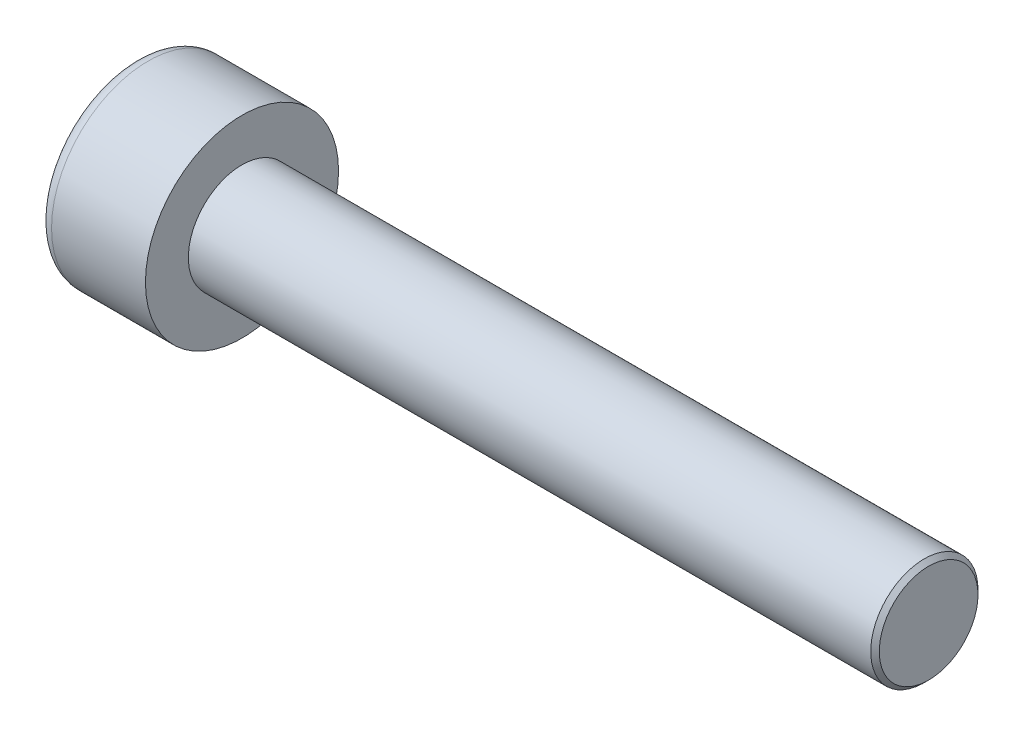
SolidWorks part; units mm, degrees
ref_plane "Front" through (0, 0, 0) normal (0, 0, 1) x (1, 0, 0)
ref_plane "Top" through (0, 0, 0) normal (0, 1, 0) x (1, 0, 0)
ref_plane "Right" through (0, 0, 0) normal (1, 0, 0) x (0, 0, -1)
sketch "Sketch1" plane through (0, 0, 0) normal (1, 0, 0) x (0, 0, -1)
  circle A0 centre (0, 0) radius 2.25
  dimension "dk" = 4.5
extrude "BaseHead" add sketch "Sketch1" along normal blind 2.5
sketch "Sketch2" plane through (2.5, 0, 0) normal (1, 0, 0) x (0, 0, -1)
  circle A0 centre (0, 0) radius 1.25
  dimension "d" = 2.5
extrude "BaseBody" add sketch "Sketch2" along normal blind 16
cosmetic thread "ThreadCosmetic1" [suppressed] parameters "b"=16, "D2"=2.013
sketch "Sketch3" plane through (0, 0, 0) normal (1, 0, 0) x (0, 0, -1)
  line L1 (1.1547, 0) -> (0.5774, 1)
  line L2 (0.5774, 1) -> (-0.5774, 1)
  line L3 (-0.5774, 1) -> (-1.1547, 0)
  line L4 (-1.1547, 0) -> (-0.5774, -1)
  line L5 (-0.5774, -1) -> (0.5774, -1)
  line L6 (0.5774, -1) -> (1.1547, 0)
  circle A0 centre (0, 0) radius 1 construction
  dimension "s" = 2
  dimension "e" = 2.3094
extrude "HexagonSocket" cut sketch "Sketch3" along normal blind 1.1
sketch "Sketch4" plane through (-4.1961, 0.75, 0) normal (0, 0, 1) x (-1, 0, 0)
  line L0 (-5.2961, 1.75) -> (-5.8735, 0.75)
  line L2 (-5.8735, 0.75) -> (-5.2961, 0.75)
  line L3 (-5.2961, 0.75) -> (-5.2961, 1.75)
  line L4 (-5.0351, 0.75) -> (0.839, 0.75) construction
  line L5 (-22.6961, 0.75) -> (-6.6961, 0.75) construction
  line L6 (-6.6961, 0.75) -> (-4.1961, 0.75) construction
  dimension "m" = 60
revolve "Cut-Revolve1" cut sketch "Sketch4" angle 360 about L4
fillet "HeadFillet" [suppressed] radius 0.1
fillet "TopFillet" radius 0.3125 1 edges at (0, 0, -2.25)
chamfer "Chamfer1" distance 0.1 angle 45 1 edges at (18.5, 0, -1.25)
sketch "Sketch5" plane through (0, 0, 0) normal (0, 0, 1) x (1, 0, 0)
  line L0 (18.4, 1.0391) -> (18.5217, 1.25)
  line L1 (18.5217, 1.25) -> (18.5217, 1.4935)
  line L2 (18.5217, 1.4935) -> (18.2782, 1.4935)
  line L3 (18.2782, 1.4935) -> (18.2782, 1.25)
  line L4 (18.2782, 1.25) -> (18.4, 1.0391)
  line L5 (0, 0) -> (7.8886, 0) construction
  line L6 (18.4, -1.25) -> (18.4, 1.25) construction
  dimension "D1" = 2.5
  dimension "D2" = 0.2435
revolve "Cut-Revolve10" [suppressed] cut sketch "Sketch5" angle 360 about L5
pattern_linear "LPattern10" [suppressed] count 55 spacing 0.2922 along (1, 0, 0)
equation "\"r1@TopFillet\" = \"d@Sketch2\" / 8"
equation "\"D1@Chamfer1\" = \"r@HeadFillet\""
equation "\"D1@Sketch5\" = \"d@Sketch2\""
equation "\"D2@Sketch5\" =  ( \"d@Sketch2\" - \"D2@ThreadCosmetic1\" )  / 2"
equation "\"D3@LPattern10\" = \"D2@Sketch5\" * 1.2"
equation "\"D1@LPattern10\" = \"b@ThreadCosmetic1\" / \"D3@LPattern10\""
